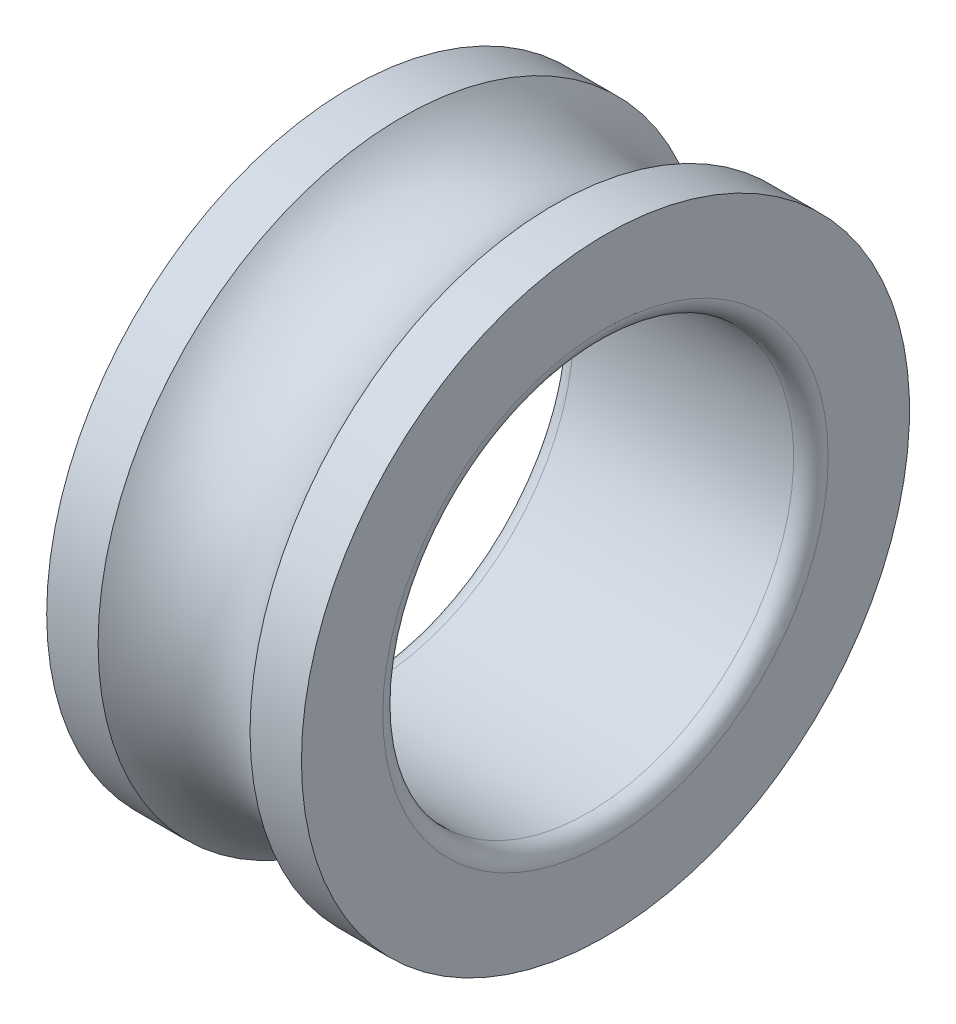
SolidWorks part; units mm, degrees
ref_plane "Front Plane" through (0, 0, 0) normal (0, 0, 1) x (1, 0, 0)
ref_plane "Top Plane" through (0, 0, 0) normal (0, 1, 0) x (1, 0, 0)
ref_plane "Right Plane" through (0, 0, 0) normal (1, 0, 0) x (0, 0, -1)
sketch "Sketch2" plane through (0, 0, 0) normal (0, 0, 1) x (1, 0, 0)
  line L0 (-24.7614, 0) -> (38.2055, 0) construction
  line L1 (0, -5.7524) -> (0, 34.5113) construction
  line L2 (9.2443, 37) -> (15.5, 37)
  line L3 (-15.5, 37) -> (-9.2443, 37)
  line L4 (-15.5, 37) -> (-15.5, 27.1)
  line L5 (-13.4, 25) -> (13.4, 25)
  line L6 (15.5, 37) -> (15.5, 27.1)
  line L7 (-15.5, 37) -> (15.5, 25) construction
  line L8 (-15.5, 25) -> (15.5, 37) construction
  arc A0 (-9.2443, 37) -> (9.2443, 37) centre (0, 44.6514) ccw
  arc A1 (13.4, 25) -> (15.5, 27.1) centre (13.4, 27.1) ccw
  arc A2 (-15.5, 27.1) -> (-13.4, 25) centre (-13.4, 27.1) ccw
  point P5 (0, 31)
  dimension "D4" = 24
  dimension "D5" = 2.1
  dimension "D1" = 31
  dimension "D2" = 25
  dimension "D3" = 37
revolve "Revolve1" add sketch "Sketch2" angle 360 about L0
